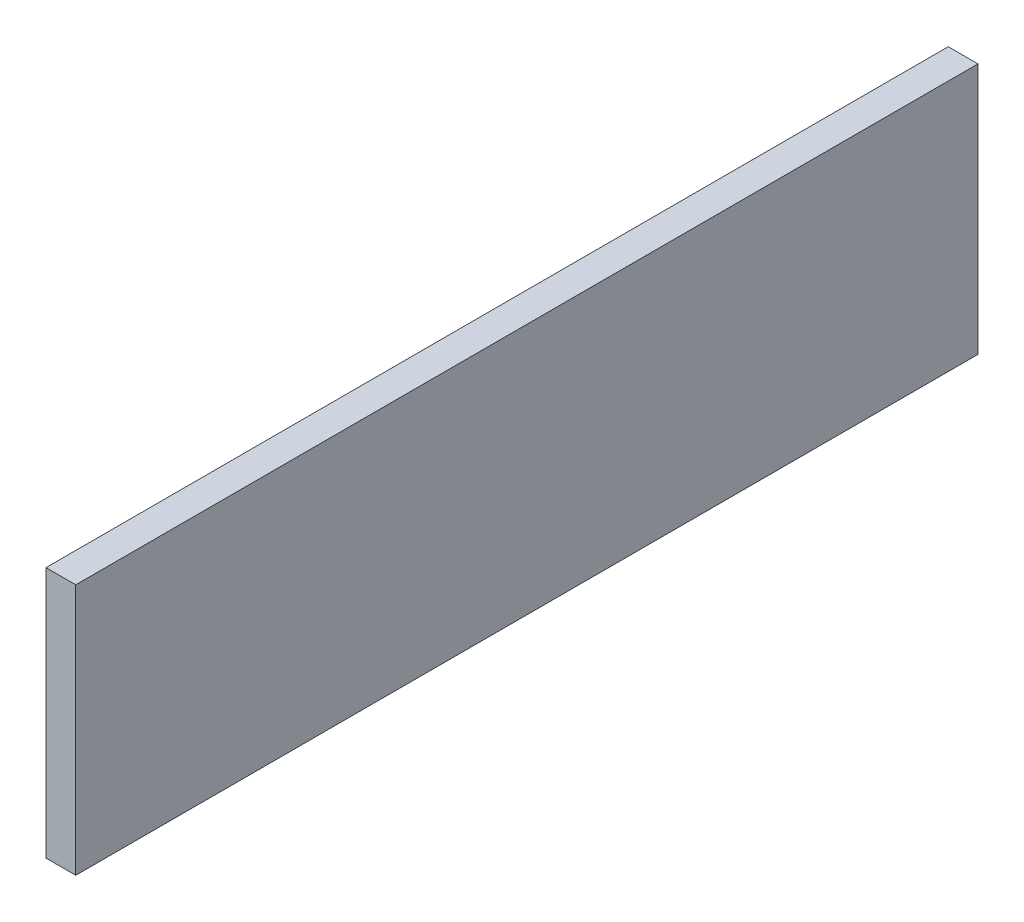
SolidWorks part; units mm, degrees
ref_plane "Front" through (0, 0, 0) normal (0, 0, 1) x (1, 0, 0)
ref_plane "Top" through (0, 0, 0) normal (0, 1, 0) x (1, 0, 0)
ref_plane "Right" through (0, 0, 0) normal (1, 0, 0) x (0, 0, -1)
sketch "Sketch1" plane through (0, 0, 0) normal (0, 1, 0) x (1, 0, 0)
  line L1 (0, 0) -> (76.2, 0)
  line L2 (0, 0) -> (0, 2311.4)
  line L3 (0, 2311.4) -> (76.2, 2311.4)
  line L4 (76.2, 0) -> (76.2, 2311.4)
  dimension "D1" = 2311.4
  dimension "D2" = 76.2
extrude "Boss-Extrude1" add sketch "Sketch1" along normal blind 644.525
